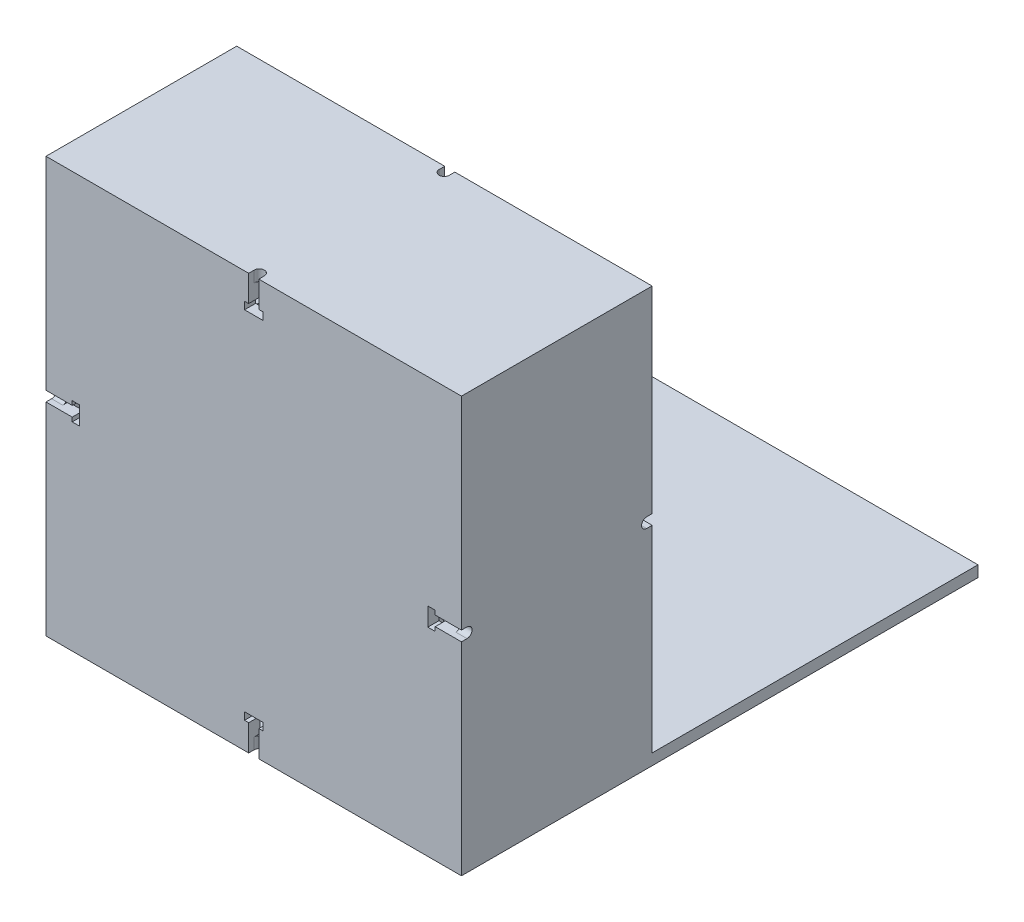
SolidWorks part; units mm, degrees
ref_plane "Piano frontale" through (0, 0, 0) normal (0, 0, 1) x (1, 0, 0)
ref_plane "Piano superiore" through (0, 0, 0) normal (0, 1, 0) x (1, 0, 0)
ref_plane "Piano destro" through (0, 0, 0) normal (1, 0, 0) x (0, 0, -1)
sketch "Schizzo2" plane through (0, 0, 0) normal (0, 0, 1) x (1, 0, 0)
  line L1 (0, 0) -> (123.3, 0)
  line L2 (0, 0) -> (0, 123.3)
  line L3 (0, 123.3) -> (123.3, 123.3)
  line L4 (123.3, 0) -> (123.3, 123.3)
extrude "Estrusione-Estrusione2" add sketch "Schizzo2" against normal blind 53.3
shell "Svuota1" thickness 3.3
sketch3d "Schizzo3D1"
  line L1 (123.3, 0, 0) -> (123.3, 123.3, 0) construction
  line L4 (123.3, 60.15, -1.65) -> (123.3, 60.15, 0)
  line L6 (123.3, 63.15, 0) -> (123.3, 60.15, 0)
  line L7 (123.3, 63.15, -1.65) -> (123.3, 63.15, 0)
  arc A2 (123.3, 63.15, -1.65) -> (123.3, 60.15, -1.65) centre (123.3, 61.65, -1.65) cw
  point P11 (121.8, 61.65, -1.65)
extrude "Taglio-Estrusione2" cut sketch "Schizzo3D1" along direction (1, 0, 0) on the side against the normal blind 3.3
sketch "Schizzo3" plane through (0, 0, 0) normal (0, 0, 1) x (1, 0, 0)
  line L0 (61.65, 0) -> (61.65, 123.3)
  line L1 (0, 0) -> (123.3, 0) construction
  line L2 (123.3, 123.3) -> (0, 123.3) construction
  line L3 (61.65, 61.65) -> (123.3, 0)
  line L4 (61.65, 61.65) -> (123.3, 123.3)
sketch "Schizzo6" plane through (0, 0, 0) normal (0, 0, 1) x (1, 0, 0)
  line L0 (120, 60.15) -> (115.51, 60.15)
  line L1 (115.51, 60.15) -> (115.51, 58.92)
  line L2 (115.51, 58.92) -> (113.3, 58.92)
  line L3 (120, 63.15) -> (115.51, 63.15)
  line L4 (115.51, 63.15) -> (115.51, 64.38)
  line L5 (115.51, 64.38) -> (113.3, 64.38)
  line L6 (113.3, 64.38) -> (113.3, 58.92)
  line L7 (120, 63.15) -> (120, 60.15)
  line L8 (61.65, 0) -> (61.65, 123.3)
  line L9 (3.3, 63.15) -> (3.3, 60.15)
  line L10 (10, 64.38) -> (10, 58.92)
  line L11 (7.79, 64.38) -> (10, 64.38)
  line L12 (7.79, 63.15) -> (7.79, 64.38)
  line L13 (3.3, 63.15) -> (7.79, 63.15)
  line L14 (7.79, 58.92) -> (10, 58.92)
  line L15 (7.79, 60.15) -> (7.79, 58.92)
  line L16 (3.3, 60.15) -> (7.79, 60.15)
  line L17 (61.65, 61.65) -> (123.3, 0)
  line L18 (61.65, 61.65) -> (123.3, 123.3)
  line L19 (60.15, 3.3) -> (63.15, 3.3)
  line L20 (58.92, 10) -> (64.38, 10)
  line L21 (58.92, 7.79) -> (58.92, 10)
  line L22 (60.15, 7.79) -> (58.92, 7.79)
  line L23 (60.15, 3.3) -> (60.15, 7.79)
  line L24 (64.38, 7.79) -> (64.38, 10)
  line L25 (63.15, 7.79) -> (64.38, 7.79)
  line L26 (63.15, 3.3) -> (63.15, 7.79)
  line L27 (63.15, 120) -> (60.15, 120)
  line L28 (64.38, 113.3) -> (58.92, 113.3)
  line L29 (64.38, 115.51) -> (64.38, 113.3)
  line L30 (63.15, 115.51) -> (64.38, 115.51)
  line L31 (63.15, 120) -> (63.15, 115.51)
  line L32 (58.92, 115.51) -> (58.92, 113.3)
  line L33 (60.15, 115.51) -> (58.92, 115.51)
  line L34 (60.15, 120) -> (60.15, 115.51)
extrude "Taglio-Estrusione6" cut sketch "Schizzo6" against normal blind 3.3 contours L34 L33 L32 L28 L29 L30 L31 L27 | L6 L2 L1 L0 L7 L3 L4 L5 | L21 L20 L24 L25 L26 L19 L23 L22 | L9 L16 L15 L14 L10 L11 L12 L13
sketch3d "Schizzo3D6"
  line L3 (0, 123.3, 0) -> (0, 0, 0) construction
  line L5 (0, 61.65, 0) -> (0, 60.15, 0)
  line L6 (0, 60.15, 0) -> (0, 60.15, -1.65)
  line L7 (0, 61.65, 0) -> (0, 63.1498, 0)
  line L8 (0, 63.1498, 0) -> (0, 63.1498, -1.623)
  arc A1 (0, 60.15, -1.65) -> (0, 63.1498, -1.623) centre (0, 61.65, -1.65) cw
  point P3 (1.5, 61.65, -1.65)
extrude "Taglio-Estrusione7" cut sketch "Schizzo3D6" along direction (1, 0, 0) on the side of the normal blind 3.3
sketch3d "Schizzo3D7"
  line L1 (60.15, 0, 0) -> (63.1517, 0, 0)
  line L2 (0, 0, 0) -> (123.3, 0, 0) construction
  line L3 (60.15, 0, 0) -> (60.15, 0, -1.65)
  line L4 (63.1517, 0, 0) -> (63.15, 0, -1.6515)
  arc A1 (63.15, 0, -1.6515) -> (60.15, 0, -1.65) centre (61.65, 0, -1.65) cw
  point P12 (61.65, 1.5, -1.65)
extrude "Taglio-Estrusione8" cut sketch "Schizzo3D7" along a picked direction on the side against the normal blind 3.3
sketch3d "Schizzo3D8"
  line L1 (63.15, 123.3, 0) -> (60.15, 123.3, 0)
  line L2 (123.3, 123.3, 0) -> (0, 123.3, 0) construction
  line L3 (63.15, 123.3, 0) -> (63.15, 123.3, -1.65)
  line L4 (60.15, 123.3, 0) -> (60.15, 123.3, -1.65)
  arc A1 (60.15, 123.3, -1.65) -> (63.15, 123.3, -1.65) centre (61.65, 123.3, -1.65) cw
  point P2 (61.65, 121.8, -1.65)
extrude "Taglio-Estrusione9" cut sketch "Schizzo3D8" along a picked direction on the side against the normal blind 3.3
sketch3d "Schizzo3D9"
  line L0 (120, 3.3, -53.3) -> (123.3, 3.3, -53.3)
  line L1 (123.3, 0, -53.3) -> (123.3, 123.3, -53.3) construction
  line L2 (123.3, 3.3, -53.3) -> (123.3, 0, -53.3)
  line L3 (123.3, 0, -53.3) -> (0, 0, -53.3)
  line L4 (3.3, 3.3, -53.3) -> (0, 3.3, -53.3)
  line L5 (0, 123.3, -53.3) -> (0, 0, -53.3) construction
  line L6 (0, 3.3, -53.3) -> (0, 0, -53.3)
  line L7 (3.3, 3.3, -53.3) -> (120, 3.3, -53.3)
extrude "Estrusione-Estrusione5" add sketch "Schizzo3D9" along direction (0, 0, 1) on the side against the normal blind 100
sketch3d "Schizzo3D10"
  line L0 (123.3, 123.3, -53.3) -> (123.3, 123.3, -56.6)
  line L1 (123.3, 123.3, -56.6) -> (123.3, 3.3, -56.6)
  line L2 (123.3, 3.3, -53.3) -> (123.3, 3.3, -153.3) construction
  line L3 (123.3, 3.3, -56.6) -> (123.3, 3.3, -53.3)
  line L4 (123.3, 3.3, -53.3) -> (123.3, 123.3, -53.3)
extrude "Estrusione-Estrusione7" add sketch "Schizzo3D10" along a picked direction on the side of the normal blind 123.3
sketch "Schizzo14" plane through (0, 0, 0) normal (-1, 0, 0) x (0, 0, 1)
  line L0 (-56.6, 64.8) -> (-56.6, 61.8)
  line L1 (-56.6, 123.3) -> (-56.6, 3.3) construction
  line L3 (-56.6, 64.8) -> (-54.95, 64.8)
  line L5 (-54.95, 61.8) -> (-56.6, 61.8)
  arc A1 (-54.95, 64.8) -> (-54.95, 61.8) centre (-54.95, 63.3) cw
extrude "Taglio-Estrusione19" cut sketch "Schizzo14" against normal blind 3.3
sketch "Schizzo17" plane through (123.3, 0, 0) normal (1, 0, 0) x (0, 0, -1)
  line L0 (56.6, 64.8) -> (56.6, 61.8)
  line L1 (56.6, 123.3) -> (56.6, 3.3) construction
  line L2 (56.6, 64.8) -> (54.95, 64.8)
  line L4 (54.95, 61.8) -> (56.6, 61.8)
  arc A1 (54.95, 61.8) -> (54.95, 64.8) centre (54.95, 63.3) cw
sketch "Schizzo21" plane through (0, 0, 0) normal (0, -1, 0) x (-1, 0, 0)
  line L0 (-64.3359, 56.8484) -> (-64.3359, 55.1984)
  line L1 (-64.3359, 56.8484) -> (-61.3359, 56.8484)
  line L2 (-61.3359, 55.1984) -> (-61.3359, 56.8484)
  arc A1 (-61.3359, 55.1984) -> (-64.3359, 55.1984) centre (-62.8359, 55.1984) cw
extrude "Taglio-Estrusione20" cut sketch "Schizzo21" against normal blind 3.3
extrude "Taglio-Estrusione21" cut sketch "Schizzo17" against normal blind 3.3
sketch "Schizzo24" plane through (0, 123.3, 0) normal (0, 1, 0) x (1, 0, 0)
  line L0 (61.7344, 56.604) -> (61.7344, 54.954)
  line L2 (64.7344, 54.954) -> (64.7344, 56.604)
  line L3 (61.7344, 56.604) -> (64.7344, 56.604)
  arc A1 (64.7344, 54.954) -> (61.7344, 54.954) centre (63.2344, 54.954) cw
extrude "Taglio-Estrusione22" cut sketch "Schizzo24" against normal blind 3.3
sketch "Schizzo26" plane through (0, 0, -56.6) normal (0, 0, -1) x (-1, 0, 0)
  line L0 (-61.7344, 120) -> (-61.7344, 115.51)
  line L1 (-61.7344, 115.51) -> (-60.5044, 115.51)
  line L2 (-60.5044, 115.51) -> (-60.5044, 113.3)
  line L3 (-60.5044, 113.3) -> (-65.9644, 113.3)
  line L4 (-65.9644, 113.3) -> (-65.9644, 115.51)
  line L5 (-65.9644, 115.51) -> (-64.7344, 115.51)
  line L6 (-64.7344, 115.51) -> (-64.7344, 120)
  line L7 (-64.7344, 120) -> (-61.7344, 120)
extrude "Taglio-Estrusione23" cut sketch "Schizzo26" against normal blind 3.3
sketch "Schizzo28" plane through (0, 0, -56.6) normal (0, 0, -1) x (-1, 0, 0)
  line L0 (-120, 61.8) -> (-115.51, 61.8)
  line L1 (-115.51, 61.8) -> (-115.51, 60.57)
  line L2 (-115.51, 60.57) -> (-113.3, 60.57)
  line L3 (-113.3, 60.57) -> (-113.3, 66.03)
  line L4 (-113.3, 66.03) -> (-115.51, 66.03)
  line L5 (-115.51, 66.03) -> (-115.51, 64.8)
  line L6 (-115.51, 64.8) -> (-120, 64.8)
  line L7 (-120, 64.8) -> (-120, 61.8)
  line L8 (-3.3, 64.8) -> (-7.79, 64.8)
  line L9 (-7.79, 64.8) -> (-7.79, 66.03)
  line L10 (-7.79, 66.03) -> (-10, 66.03)
  line L11 (-10, 66.03) -> (-10, 60.57)
  line L12 (-10, 60.57) -> (-7.79, 60.57)
  line L13 (-7.79, 60.57) -> (-7.79, 61.8)
  line L14 (-7.79, 61.8) -> (-3.3, 61.8)
  line L15 (-3.3, 61.8) -> (-3.3, 64.8)
  line L16 (-64.3359, 3.3) -> (-64.3359, 7.79)
  line L17 (-64.3359, 7.79) -> (-65.5659, 7.79)
  line L18 (-65.5659, 7.79) -> (-65.5659, 10)
  line L19 (-65.5659, 10) -> (-60.1059, 10)
  line L20 (-60.1059, 10) -> (-60.1059, 7.79)
  line L21 (-60.1059, 7.79) -> (-61.3359, 7.79)
  line L22 (-61.3359, 7.79) -> (-61.3359, 3.3)
  line L23 (-61.3359, 3.3) -> (-64.3359, 3.3)
extrude "Taglio-Estrusione24" cut sketch "Schizzo28" against normal blind 3.3
